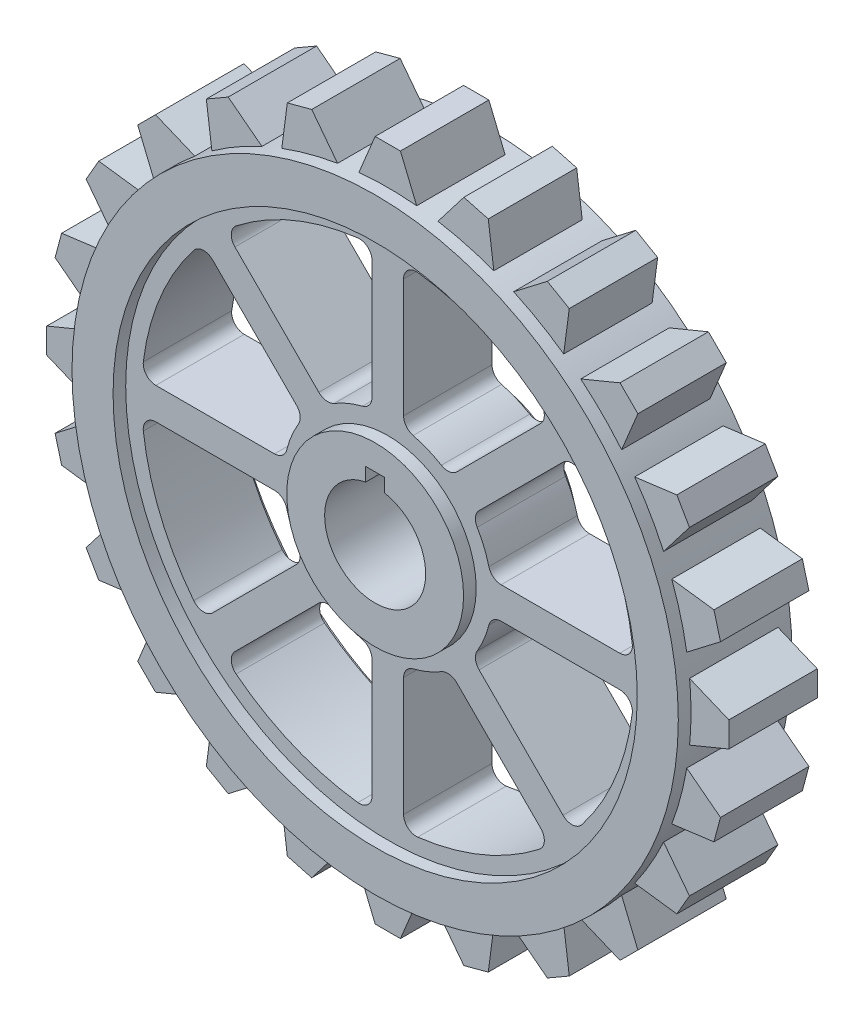
SolidWorks part; units mm, degrees
ref_plane "Front Plane" through (0, 0, 0) normal (0, 0, 1) x (1, 0, 0)
ref_plane "Top Plane" through (0, 0, 0) normal (0, 1, 0) x (1, 0, 0)
ref_plane "Right Plane" through (0, 0, 0) normal (1, 0, 0) x (0, 0, -1)
sketch "Sketch1" plane through (0, 0, 0) normal (0, 0, 1) x (1, 0, 0)
  line L0 (-1.5, 7.8581) -> (-1.5, 10)
  line L1 (-1.5, 10) -> (1.5, 10)
  line L2 (1.5, 10) -> (1.5, 7.8581)
  line L3 (0, 0) -> (0, 10) construction
  circle A0 centre (0, 0) radius 48
  arc A1 (-1.5, 7.8581) -> (1.5, 7.8581) centre (0, 0) ccw
  point P3 (0, 0)
  point P9 (0, 0)
  point P10 (0, 10)
  dimension "D1" = 96
  dimension "D2" = 8
  dimension "D3" = 10
  dimension "D4" = 3
extrude "Boss-Extrude1" add sketch "Sketch1" along normal mid plane 18
sketch "Sketch2" plane through (0, 0, 9) normal (0, 0, 1) x (1, 0, 0)
  circle A0 centre (0, 0) radius 14
  circle A1 centre (0, 0) radius 41.5
  dimension "D1" = 83
  dimension "D2" = 28
extrude "Cut-Extrude1" cut sketch "Sketch2" against normal blind 2
mirror "Mirror1" about plane through (0, 0, 0) normal (0, 0, 1) of "Cut-Extrude1"
sketch "Sketch3" plane through (0, 0, 7) normal (0, 0, 1) x (1, 0, 0)
  line L0 (0, 14) -> (0, 41.5) construction
  line L1 (-9.8995, 9.8995) -> (-29.3449, 29.3449) construction
  line L2 (-10.9208, 14.4563) -> (-24.201, 27.7365)
  line L3 (-2.5, 17.9444) -> (-2.5, 36.7253)
  line L4 (-9.7648, 13.3003) -> (-25.7527, 29.2882) construction
  line L5 (-2.5, 16.3095) -> (-2.5, 38.9198) construction
  circle A0 centre (0, 0) radius 14 construction
  circle A1 centre (0, 0) radius 41.5 construction
  circle A2 centre (0, 0) radius 41.5 construction
  circle A3 centre (0, 0) radius 14 construction
  arc A4 (0, 14) -> (-9.8995, 9.8995) centre (0, 0) ccw construction
  arc A5 (0, 41.5) -> (-29.3449, 29.3449) centre (0, 0) ccw construction
  arc A6 (-4.7432, 38.7105) -> (-24.0185, 30.7264) centre (0, 0) ccw
  arc A7 (-4.0135, 16.0044) -> (-8.4789, 14.1548) centre (0, 0) ccw
  arc A8 (-2.5, 16.3095) -> (-9.7648, 13.3003) centre (0, 0) ccw construction
  arc A9 (-10.9208, 14.4563) -> (-8.4789, 14.1548) centre (-9.5066, 15.8706) ccw
  arc A10 (-2.5, 17.9444) -> (-4.0135, 16.0044) centre (-4.5, 17.9444) cw
  arc A11 (-2.5, 38.9198) -> (-25.7527, 29.2882) centre (0, 0) ccw construction
  arc A12 (-4.7432, 38.7105) -> (-2.5, 36.7253) centre (-4.5, 36.7253) cw
  arc A13 (-24.201, 27.7365) -> (-24.0185, 30.7264) centre (-22.7868, 29.1507) cw
  dimension "D3" = 2
  dimension "D1" = 45
  dimension "D2" = 2.5
extrude "Cut-Extrude2" cut sketch "Sketch3" against normal through all
pattern_circular "CirPattern2" count 8 over 360 about axis through (0, 0, 0) along (0, 0, 1) of "Cut-Extrude2"
sketch "Sketch5" plane through (0, 0, 0) normal (0, 0, 1) x (1, 0, 0)
  line L0 (-4.5758, 47.7814) -> (-2, 54)
  line L1 (-2, 54) -> (2, 54)
  line L2 (2, 54) -> (4.5758, 47.7814)
  line L3 (0, 48) -> (0, 54) construction
  circle A0 centre (0, 0) radius 48 construction
  arc A1 (4.5758, 47.7814) -> (-4.5758, 47.7814) centre (0, 0) ccw
  dimension "D1" = 6
  dimension "D2" = 4
  dimension "D3" = 45
extrude "Boss-Extrude2" add sketch "Sketch5" along normal mid plane 14
pattern_circular "CirPattern3" count 24 over 360 about axis through (0, 0, 0) along (0, 0, 1) of "Boss-Extrude2"
